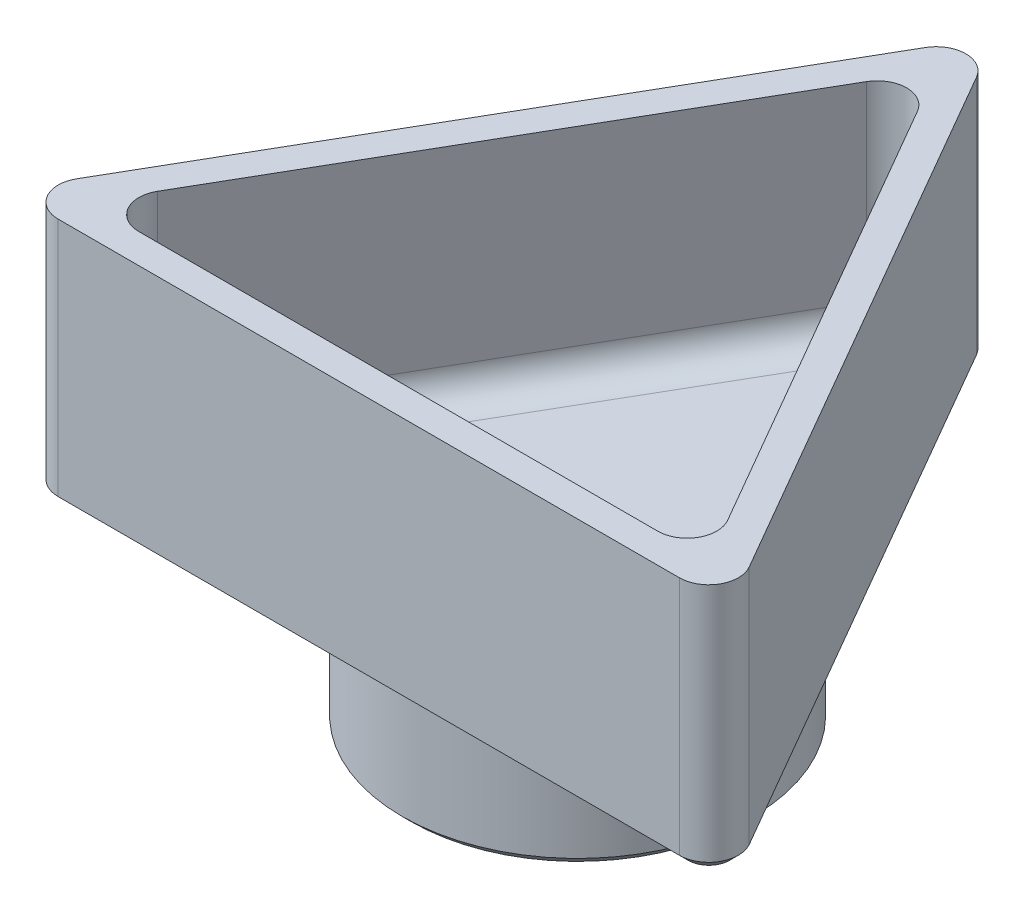
SolidWorks part; units mm, degrees
material "PLA"
ref_plane "Front Plane" through (0, 0, 0) normal (0, 0, 1) x (1, 0, 0)
ref_plane "Top Plane" through (0, 0, 0) normal (0, 1, 0) x (1, 0, 0)
ref_plane "Right Plane" through (0, 0, 0) normal (1, 0, 0) x (0, 0, -1)
sketch "Sketch1" plane through (0, 0, 0) normal (0, 1, 0) x (1, 0, 0)
  line L3 (0, 35.9169) -> (31.1049, -17.9584)
  line L4 (31.1049, -17.9584) -> (-31.1049, -17.9584)
  line L5 (-31.1049, -17.9584) -> (0, 35.9169)
  circle A0 centre (0, 0) radius 35.9169 construction
  dimension "D1" = 71.8337
extrude "Boss-Extrude1" add sketch "Sketch1" along normal blind 21.43
shell "Shell1" thickness 2.54
sketch "Sketch3" plane through (0, 0, 0) normal (0, -1, 0) x (1, 0, 0)
  circle A0 centre (0, 0) radius 15.0813
  dimension "D1" = 30.1625
extrude "Boss-Extrude2" add sketch "Sketch3" along normal blind 11.905
fillet "Fillet1" radius 2.54 3 edges at (0, 10.715, -35.9169) (31.1049, 10.715, 17.9584) (-31.1049, 10.715, 17.9584)
fillet "Fillet2" radius 2.54 3 edges at (0, 11.985, -30.8369) (26.7055, 11.985, 15.4184) (-26.7055, 11.985, 15.4184)
fillet "Fillet3" radius 2.54 6 edges at (24.5058, 2.54, 14.1484) (0, 2.54, 15.4184) (-24.5058, 2.54, 14.1484) (-13.3528, 2.54, -7.7092) (0, 2.54, -28.2969) (13.3528, 2.54, -7.7092)
chamfer "Chamfer2" distance 0.762 angle 45 6 edges at (-28.9052, 0, 16.6884) (0, 0, 17.9584) (-15.5525, 0, -8.9792) (28.9052, 0, 16.6884) (0, 0, -33.3769) (15.5525, 0, -8.9792)
sketch "Sketch5" plane through (0, -11.905, 0) normal (0, -1, 0) x (1, 0, 0)
  circle A2 centre (0, 0) radius 12.5412
  circle A3 centre (0, 0) radius 12.5413
  dimension "D1" = 2.54
extrude "Cut-Extrude1" cut sketch "Sketch5" against normal up to surface (11.905 mm away) up to face at (0, 0, 0)
chamfer "Chamfer3" distance 0.762 angle 45 1 edges at (0, -11.905, -15.0813)
